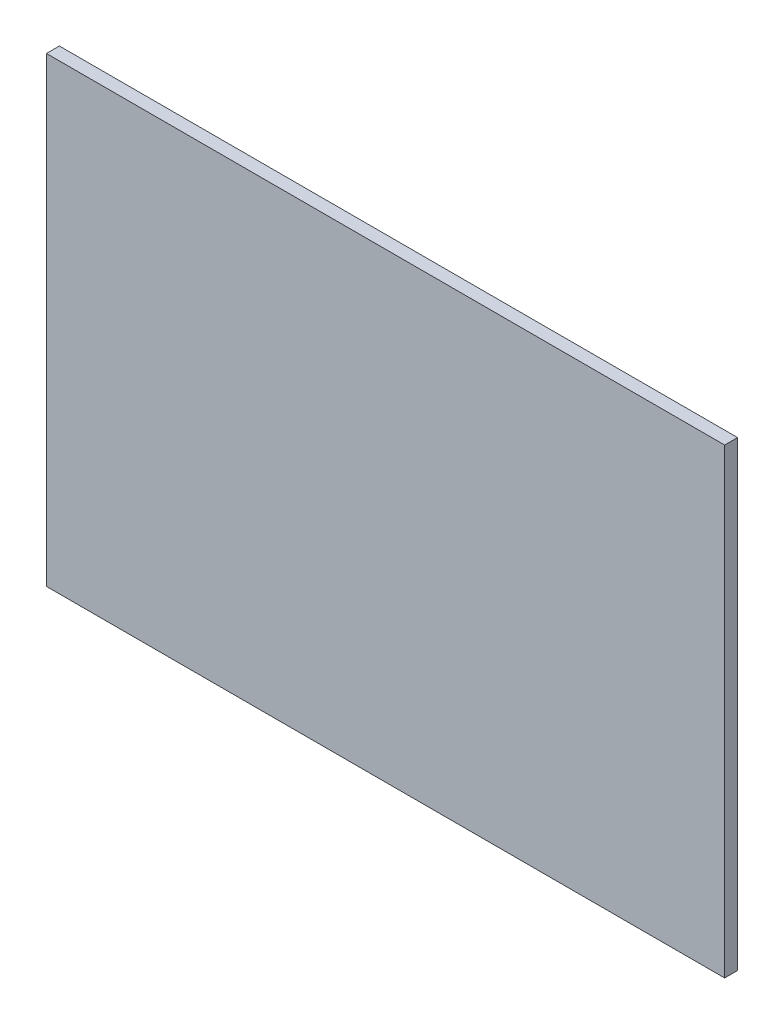
SolidWorks part; units mm, degrees
ref_plane "Front Plane" through (0, 0, 0) normal (0, 0, 1) x (1, 0, 0)
ref_plane "Top Plane" through (0, 0, 0) normal (0, 1, 0) x (1, 0, 0)
ref_plane "Right Plane" through (0, 0, 0) normal (1, 0, 0) x (0, 0, -1)
sketch "Sketch1" plane through (0, 0, 0) normal (0, 0, 1) x (1, 0, 0)
  line L0 (-670, 746) -> (-670, 0) construction
  line L1 (-670, 713.3) -> (330, 713.3)
  line L2 (-670, 713.3) -> (-670, 32.7)
  line L3 (-670, 32.7) -> (330, 32.7)
  line L4 (330, 713.3) -> (330, 32.7)
  line L5 (330, 746) -> (330, 0) construction
  line L6 (-670, 726) -> (330, 726) construction
  line L7 (-670, 20) -> (330, 20) construction
  dimension "D1" = 12.7
  dimension "D2" = 12.7
extrude "Boss-Extrude1" add sketch "Sketch1" along normal blind 19.05
